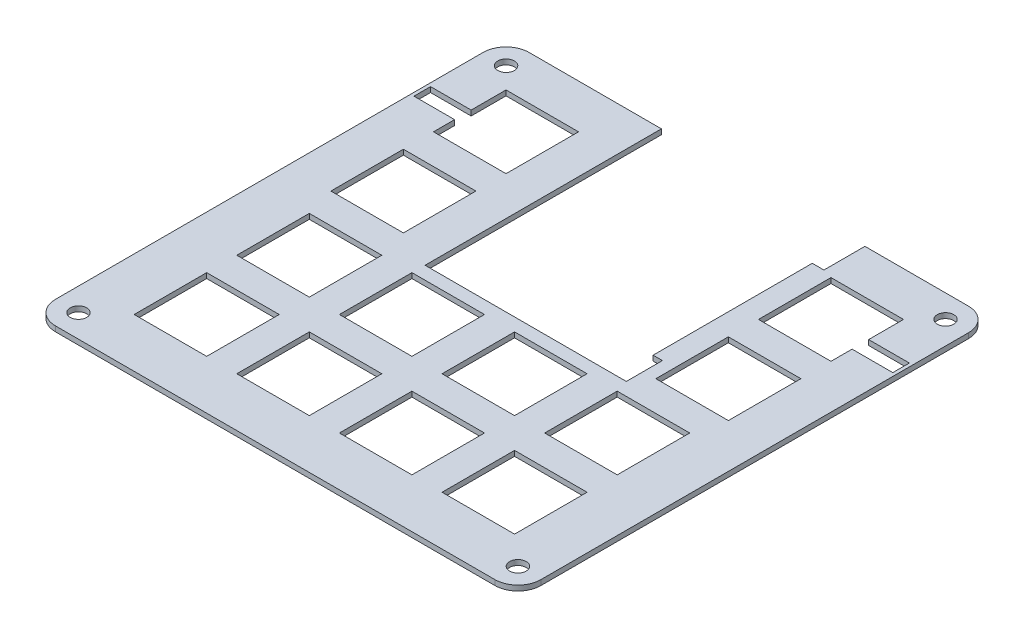
SolidWorks part; units mm, degrees
ref_plane "Front Plane" through (0, 0, 0) normal (0, 0, 1) x (1, 0, 0)
ref_plane "Top Plane" through (0, 0, 0) normal (0, 1, 0) x (1, 0, 0)
ref_plane "Right Plane" through (0, 0, 0) normal (1, 0, 0) x (0, 0, -1)
sketch "Sketch2" plane through (0, 0, 0) normal (0, 1, 0) x (1, 0, 0)
  line L6 (-46.8585, -41.275) -> (-46.8585, 41.275)
  line L8 (46.8585, -41.275) -> (46.8585, 41.275)
  line L9 (42.418, -45.7155) -> (-42.418, -45.7155)
  line L10 (-42.418, 45.7155) -> (-16.8754, 45.7155)
  line L12 (22.418, 41.275) -> (22.418, 39.575)
  line L13 (22.418, 39.575) -> (22.418, 37.7973)
  line L16 (42.418, 27.292) -> (38.3626, 27.292)
  line L18 (42.418, 30.492) -> (38.3626, 30.492)
  line L19 (42.418, 30.492) -> (46.218, 30.492)
  line L20 (46.218, 30.492) -> (46.218, 27.292)
  line L21 (46.218, 27.292) -> (42.418, 27.292)
  line L24 (-46.218, 28.892) -> (-46.218, 30.492)
  line L25 (-46.218, 30.492) -> (-38.3754, 30.492)
  line L26 (-46.218, 28.892) -> (-46.218, 27.292)
  line L27 (-46.218, 27.292) -> (-38.3754, 27.292)
  line L29 (20.1687, 37.7973) -> (20.1687, 9.575)
  line L30 (22.418, 37.7973) -> (20.1687, 37.7973)
  line L31 (20.1687, 9.575) -> (20.1687, 7.075)
  line L32 (20.1687, 7.075) -> (21.9687, 7.075)
  line L33 (-9.9124, 0.0949) -> (21.9687, 0.0949)
  line L35 (21.9687, 7.075) -> (21.9687, 0.0949)
  line L36 (22.418, 41.275) -> (22.418, 45.7155)
  line L38 (-16.8754, 30.2189) -> (-16.8754, 0.0949)
  line L39 (-16.8754, 0.0949) -> (-9.9124, 0.0949)
  line L40 (-16.8754, 30.2189) -> (-16.8754, 45.7155)
  line L41 (-31.3754, 37.2189) -> (-38.3754, 37.2189)
  line L42 (-38.3754, 37.2189) -> (-38.3754, 23.2189)
  line L43 (-38.3754, 23.2189) -> (-24.3754, 23.2189)
  line L44 (-24.3754, 23.2189) -> (-24.3754, 37.2189)
  line L45 (-24.3754, 37.2189) -> (-31.3754, 37.2189)
  line L47 (-38.3754, 10.4069) -> (-38.3754, 17.4069)
  line L48 (-38.3754, 17.4069) -> (-24.3754, 17.4069)
  line L49 (-24.3754, 17.4069) -> (-24.3754, 3.4069)
  line L50 (-24.3754, 3.4069) -> (-38.3754, 3.4069)
  line L51 (-38.3754, 3.4069) -> (-38.3754, 10.4069)
  line L53 (-36.7244, -9.4051) -> (-36.7244, -2.4051)
  line L54 (-36.7244, -2.4051) -> (-22.7244, -2.4051)
  line L55 (-22.7244, -2.4051) -> (-22.7244, -16.4051)
  line L56 (-22.7244, -16.4051) -> (-36.7244, -16.4051)
  line L57 (-36.7244, -16.4051) -> (-36.7244, -9.4051)
  line L59 (-36.7244, -29.2171) -> (-36.7244, -22.2171)
  line L60 (-36.7244, -22.2171) -> (-22.7244, -22.2171)
  line L61 (-22.7244, -22.2171) -> (-22.7244, -36.2171)
  line L62 (-22.7244, -36.2171) -> (-36.7244, -36.2171)
  line L63 (-36.7244, -36.2171) -> (-36.7244, -29.2171)
  line L65 (-9.9124, -22.2171) -> (-2.9124, -22.2171)
  line L66 (-2.9124, -22.2171) -> (-2.9124, -36.2171)
  line L67 (-2.9124, -36.2171) -> (-16.9124, -36.2171)
  line L68 (-16.9124, -36.2171) -> (-16.9124, -22.2171)
  line L69 (-16.9124, -22.2171) -> (-9.9124, -22.2171)
  line L71 (-9.9124, -16.4051) -> (-2.9124, -16.4051)
  line L72 (-2.9124, -16.4051) -> (-2.9124, -2.4051)
  line L73 (-2.9124, -2.4051) -> (-16.9124, -2.4051)
  line L74 (-16.9124, -2.4051) -> (-16.9124, -16.4051)
  line L75 (-16.9124, -16.4051) -> (-9.9124, -16.4051)
  line L77 (9.8996, -2.4051) -> (2.8996, -2.4051)
  line L78 (2.8996, -2.4051) -> (2.8996, -16.4051)
  line L79 (2.8996, -16.4051) -> (16.8996, -16.4051)
  line L80 (16.8996, -16.4051) -> (16.8996, -2.4051)
  line L81 (16.8996, -2.4051) -> (9.8996, -2.4051)
  line L83 (9.8996, -22.2171) -> (2.8996, -22.2171)
  line L84 (2.8996, -22.2171) -> (2.8996, -36.2171)
  line L85 (2.8996, -36.2171) -> (16.8996, -36.2171)
  line L86 (16.8996, -36.2171) -> (16.8996, -22.2171)
  line L87 (16.8996, -22.2171) -> (9.8996, -22.2171)
  line L89 (36.7116, -29.2171) -> (36.7116, -22.2171)
  line L90 (36.7116, -22.2171) -> (22.7116, -22.2171)
  line L91 (22.7116, -22.2171) -> (22.7116, -36.2171)
  line L92 (22.7116, -36.2171) -> (36.7116, -36.2171)
  line L93 (36.7116, -36.2171) -> (36.7116, -29.2171)
  line L95 (29.7116, -2.4051) -> (22.7116, -2.4051)
  line L96 (22.7116, -2.4051) -> (22.7116, -16.4051)
  line L97 (22.7116, -16.4051) -> (36.7116, -16.4051)
  line L98 (36.7116, -16.4051) -> (36.7116, -2.4051)
  line L99 (36.7116, -2.4051) -> (29.7116, -2.4051)
  line L101 (38.3626, 10.4069) -> (38.3626, 17.4069)
  line L102 (38.3626, 17.4069) -> (24.3626, 17.4069)
  line L103 (24.3626, 17.4069) -> (24.3626, 3.4069)
  line L104 (24.3626, 3.4069) -> (38.3626, 3.4069)
  line L105 (38.3626, 3.4069) -> (38.3626, 10.4069)
  line L106 (38.3626, 30.2189) -> (38.3626, 23.2189)
  line L107 (38.3626, 23.2189) -> (24.3626, 23.2189)
  line L108 (24.3626, 23.2189) -> (24.3626, 37.2189)
  line L109 (24.3626, 37.2189) -> (38.3626, 37.2189)
  line L110 (38.3626, 37.2189) -> (38.3626, 30.2189)
  line L111 (22.418, 45.7155) -> (42.418, 45.7155)
  arc A0 (-42.418, 45.7155) -> (-46.8585, 41.275) centre (-42.418, 41.275) ccw
  arc A1 (42.418, 45.7155) -> (46.8585, 41.275) centre (42.418, 41.275) cw
  arc A2 (-46.8585, -41.275) -> (-42.418, -45.7155) centre (-42.418, -41.275) ccw
  arc A3 (46.8585, -41.275) -> (42.418, -45.7155) centre (42.418, -41.275) cw
  circle A4 centre (42.418, 41.275) radius 1.6
  circle A5 centre (-42.418, 41.275) radius 1.6
  circle A6 centre (-42.418, -41.275) radius 1.6
  circle A7 centre (42.418, -41.275) radius 1.6
extrude "Boss-Extrude3" add sketch "Sketch2" along normal blind 1 contours A3 L8 A1 L111 L36 L12 L13 L30 L29 L31 L32 L35 L33 L39 L38 L40 L10 A0 L6 A2 L9 A7 A6 A5 A4 L105 L104 L103 L102 L101 L99 L98 L97 L96 L95 L93 L92 L91 L90 L89 L87 L86 L85
